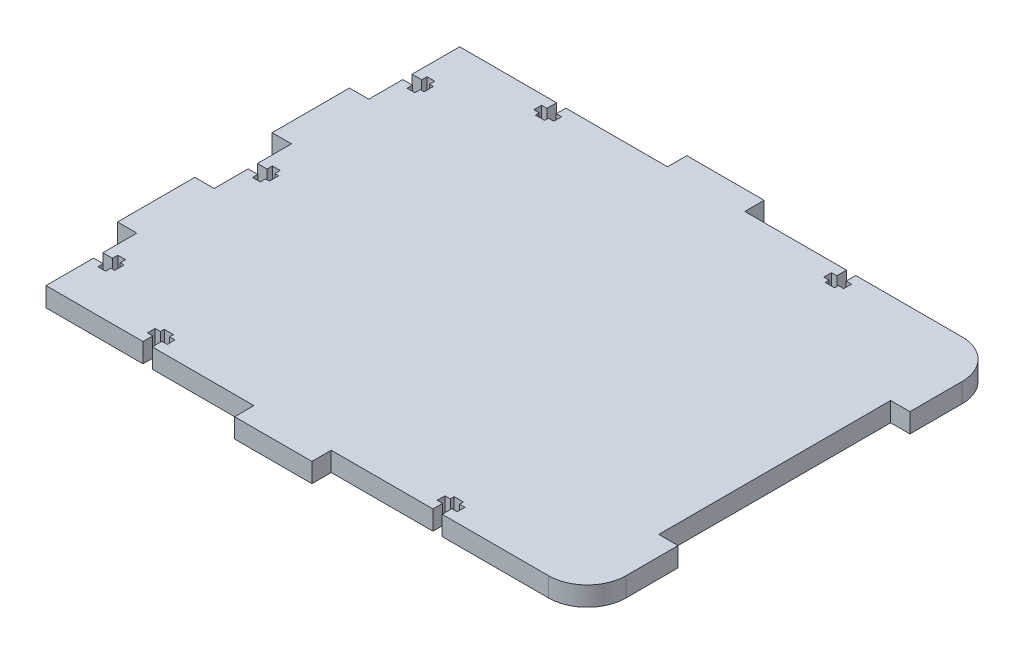
SolidWorks part; units mm, degrees
material "6061 Alloy"
ref_plane "Front Plane" through (0, 0, 0) normal (0, 0, 1) x (1, 0, 0)
ref_plane "Top Plane" through (0, 0, 0) normal (0, 1, 0) x (1, 0, 0)
ref_plane "Right Plane" through (0, 0, 0) normal (1, 0, 0) x (0, 0, -1)
sketch "Sketch1" plane through (0, 0, 0) normal (0, 1, 0) x (1, 0, 0)
  line L0 (-85.4998, 67.5755) -> (-53.6313, 67.5755)
  line L1 (-50.5834, 67.5755) -> (-17.1824, 67.5755)
  line L2 (8.2176, 67.5755) -> (41.6187, 67.5755)
  line L3 (44.6666, 67.5755) -> (79.6002, 67.5755)
  line L4 (-85.4998, -68.3145) -> (-53.6313, -68.3145)
  line L5 (-50.5834, -68.3145) -> (-17.1824, -68.3145)
  line L6 (8.2176, -68.3145) -> (41.6187, -68.3145)
  line L7 (44.6666, -68.3145) -> (79.6425, -68.3145)
  line L8 (-85.4998, 48.9065) -> (-85.4998, 37.7305)
  line L9 (-85.4998, 12.3305) -> (-85.4998, 1.1544)
  line L10 (-85.4998, -1.8935) -> (-85.4998, -13.0695)
  line L11 (-85.4998, -38.4695) -> (-85.4998, -49.6456)
  line L12 (-78.5148, 51.9544) -> (-79.7848, 51.9544)
  line L13 (-79.7848, 51.9544) -> (-79.7848, 53.707)
  line L14 (-79.7848, 53.707) -> (-82.3248, 53.707)
  line L15 (-82.3248, 53.707) -> (-82.3248, 51.9544)
  line L16 (-82.3248, 51.9544) -> (-85.4998, 51.9544)
  line L17 (-78.5148, 48.9065) -> (-79.7848, 48.9065)
  line L18 (-79.7848, 48.9065) -> (-79.7848, 47.1539)
  line L19 (-79.7848, 47.1539) -> (-82.3248, 47.1539)
  line L20 (-82.3248, 47.1539) -> (-82.3248, 48.9065)
  line L21 (-82.3248, 48.9065) -> (-85.4998, 48.9065)
  line L22 (-78.5148, 1.1544) -> (-79.7848, 1.1544)
  line L23 (-79.7848, 1.1544) -> (-79.7848, 2.907)
  line L24 (-79.7848, 2.907) -> (-82.3248, 2.907)
  line L25 (-82.3248, 2.907) -> (-82.3248, 1.1544)
  line L26 (-82.3248, 1.1544) -> (-85.4998, 1.1544)
  line L27 (-78.5148, -1.8935) -> (-79.7848, -1.8935)
  line L28 (-79.7848, -1.8935) -> (-79.7848, -3.6461)
  line L29 (-79.7848, -3.6461) -> (-82.3248, -3.6461)
  line L30 (-82.3248, -3.6461) -> (-82.3248, -1.8935)
  line L31 (-82.3248, -1.8935) -> (-85.4998, -1.8935)
  line L32 (-78.5148, -49.6456) -> (-79.7848, -49.6456)
  line L33 (-79.7848, -49.6456) -> (-79.7848, -47.893)
  line L34 (-79.7848, -47.893) -> (-82.3248, -47.893)
  line L35 (-82.3248, -47.893) -> (-82.3248, -49.6456)
  line L36 (-82.3248, -49.6456) -> (-85.4998, -49.6456)
  line L37 (-78.5148, -52.6935) -> (-79.7848, -52.6935)
  line L38 (-79.7848, -52.6935) -> (-79.7848, -54.4461)
  line L39 (-79.7848, -54.4461) -> (-82.3248, -54.4461)
  line L40 (-82.3248, -54.4461) -> (-82.3248, -52.6935)
  line L41 (-82.3248, -52.6935) -> (-85.4998, -52.6935)
  line L42 (-85.4998, 37.7305) -> (-91.8498, 37.7305)
  line L43 (-91.8498, 37.7305) -> (-91.8498, 12.3305)
  line L44 (-91.8498, 12.3305) -> (-85.4998, 12.3305)
  line L45 (-85.4998, -13.0695) -> (-91.8498, -13.0695)
  line L46 (-91.8498, -13.0695) -> (-91.8498, -38.4695)
  line L47 (-91.8498, -38.4695) -> (-85.4998, -38.4695)
  line L48 (-85.4998, 67.5755) -> (-85.4998, 51.9544)
  line L49 (-85.4998, -52.6935) -> (-85.4998, -68.3145)
  line L54 (-78.5148, 51.9544) -> (-78.5148, 48.9065)
  line L55 (-78.5148, 1.1544) -> (-78.5148, -1.8935)
  line L56 (-78.5148, -49.6456) -> (-78.5148, -52.6935)
  line L57 (85.9714, 37.7305) -> (85.9714, -38.4695)
  line L58 (85.9714, 37.7305) -> (92.3068, 37.7305)
  line L59 (92.3068, 37.7305) -> (92.3002, 54.8755)
  line L60 (85.9714, -38.4695) -> (92.3214, -38.4695)
  line L61 (92.3214, -38.4695) -> (92.3425, -55.6145)
  line L62 (-17.1824, 67.5755) -> (-17.1824, 73.9255)
  line L63 (-17.1824, 73.9255) -> (8.2176, 73.9255)
  line L64 (8.2176, 73.9255) -> (8.2176, 67.5755)
  line L65 (-17.1824, -68.3145) -> (-17.1824, -74.6645)
  line L66 (-17.1824, -74.6645) -> (8.2176, -74.6645)
  line L67 (8.2176, -74.6645) -> (8.2176, -68.3145)
  line L68 (-50.5834, 60.5905) -> (-50.5834, 61.8605)
  line L69 (-50.5834, 61.8605) -> (-48.8308, 61.8605)
  line L70 (-48.8308, 61.8605) -> (-48.8308, 64.4005)
  line L71 (-48.8308, 64.4005) -> (-50.5834, 64.4005)
  line L72 (-50.5834, 64.4005) -> (-50.5834, 67.5755)
  line L73 (-53.6313, 60.5905) -> (-53.6313, 61.8605)
  line L74 (-53.6313, 61.8605) -> (-55.3839, 61.8605)
  line L75 (-55.3839, 61.8605) -> (-55.3839, 64.4005)
  line L76 (-55.3839, 64.4005) -> (-53.6313, 64.4005)
  line L77 (-53.6313, 64.4005) -> (-53.6313, 67.5755)
  line L78 (-53.6313, 60.5905) -> (-50.5834, 60.5905)
  line L79 (44.6666, 60.5905) -> (44.6666, 61.8605)
  line L80 (44.6666, 61.8605) -> (46.4192, 61.8605)
  line L81 (46.4192, 61.8605) -> (46.4192, 64.4005)
  line L82 (46.4192, 64.4005) -> (44.6666, 64.4005)
  line L83 (44.6666, 64.4005) -> (44.6666, 67.5755)
  line L84 (41.6187, 60.5905) -> (41.6187, 61.8605)
  line L85 (41.6187, 61.8605) -> (39.8661, 61.8605)
  line L86 (39.8661, 61.8605) -> (39.8661, 64.4005)
  line L87 (39.8661, 64.4005) -> (41.6187, 64.4005)
  line L88 (41.6187, 64.4005) -> (41.6187, 67.5755)
  line L89 (41.6187, 60.5905) -> (44.6666, 60.5905)
  line L90 (-50.5834, -61.3295) -> (-50.5834, -62.5995)
  line L91 (-50.5834, -62.5995) -> (-48.8308, -62.5995)
  line L92 (-48.8308, -62.5995) -> (-48.8308, -65.1395)
  line L93 (-48.8308, -65.1395) -> (-50.5834, -65.1395)
  line L94 (-50.5834, -65.1395) -> (-50.5834, -68.3145)
  line L95 (-53.6313, -61.3295) -> (-53.6313, -62.5995)
  line L96 (-53.6313, -62.5995) -> (-55.3839, -62.5995)
  line L97 (-55.3839, -62.5995) -> (-55.3839, -65.1395)
  line L98 (-55.3839, -65.1395) -> (-53.6313, -65.1395)
  line L99 (-53.6313, -65.1395) -> (-53.6313, -68.3145)
  line L100 (-53.6313, -61.3295) -> (-50.5834, -61.3295)
  line L101 (44.6666, -61.3295) -> (44.6666, -62.5995)
  line L102 (44.6666, -62.5995) -> (46.4192, -62.5995)
  line L103 (46.4192, -62.5995) -> (46.4192, -65.1395)
  line L104 (46.4192, -65.1395) -> (44.6666, -65.1395)
  line L105 (44.6666, -65.1395) -> (44.6666, -68.3145)
  line L106 (41.6187, -61.3295) -> (41.6187, -62.5995)
  line L107 (41.6187, -62.5995) -> (39.8661, -62.5995)
  line L108 (39.8661, -62.5995) -> (39.8661, -65.1395)
  line L109 (39.8661, -65.1395) -> (41.6187, -65.1395)
  line L110 (41.6187, -65.1395) -> (41.6187, -68.3145)
  line L111 (41.6187, -61.3295) -> (44.6666, -61.3295)
  arc A0 (92.3002, 54.8755) -> (79.6002, 67.5755) centre (79.6002, 54.8755) ccw
  arc A1 (79.6425, -68.3145) -> (92.3425, -55.6145) centre (79.6425, -55.6145) ccw
extrude "Boss-Extrude1" add sketch "Sketch1" along normal blind 6.35
